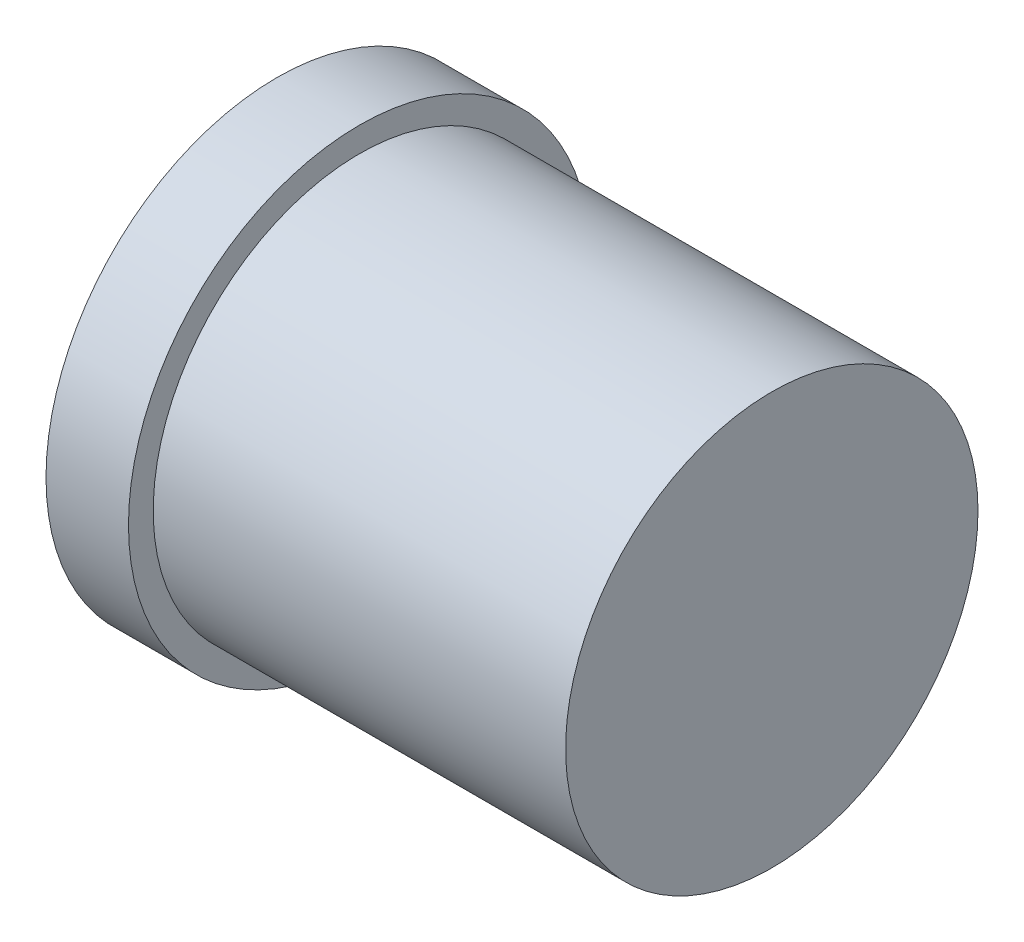
SolidWorks part; units mm, degrees
ref_plane "Front Plane" through (0, 0, 0) normal (0, 0, 1) x (1, 0, 0)
ref_plane "Top Plane" through (0, 0, 0) normal (0, 1, 0) x (1, 0, 0)
ref_plane "Right Plane" through (0, 0, 0) normal (1, 0, 0) x (0, 0, -1)
sketch "Sketch1" plane through (0, 0, 0) normal (1, 0, 0) x (0, 0, -1)
  circle A0 centre (0, 0) radius 14
extrude "Boss-Extrude1" add sketch "Sketch1" along normal blind 5
sketch "Sketch2" plane through (5, 0, 0) normal (1, 0, 0) x (0, 0, -1)
  circle A0 centre (0, 0) radius 12.5
extrude "Boss-Extrude2" add sketch "Sketch2" along normal blind 25
